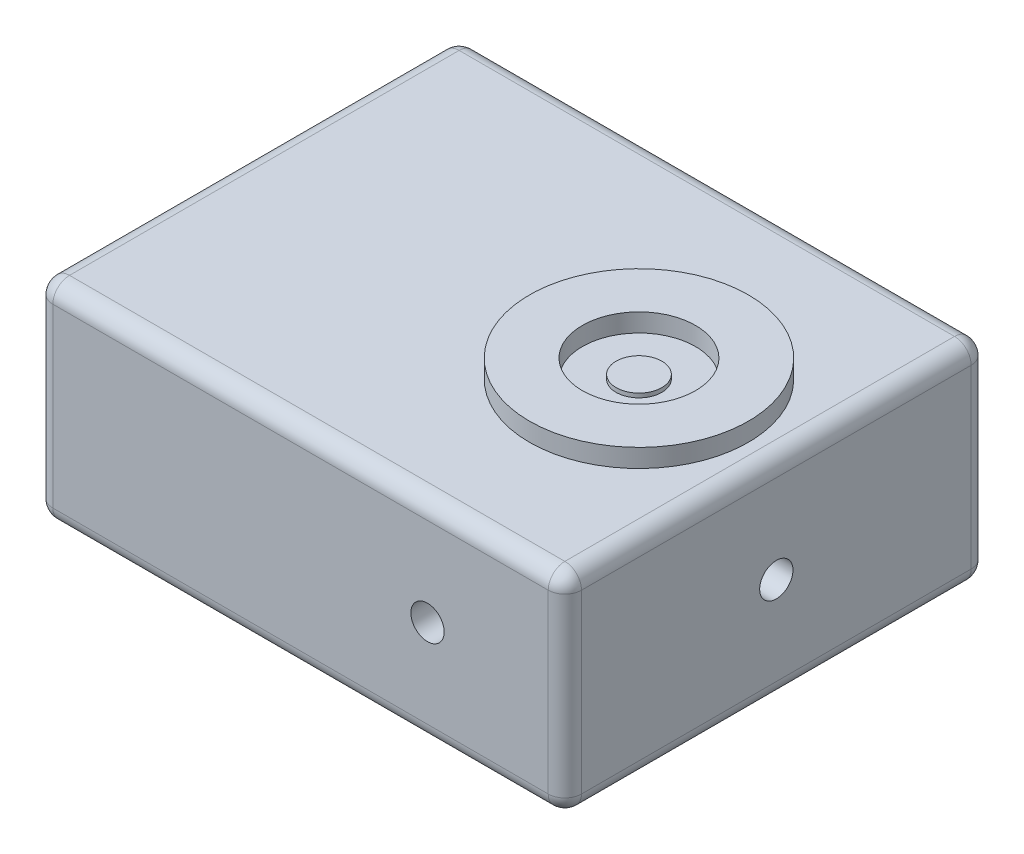
SolidWorks part; units mm, degrees
material "Stainless Steel (ferritic)"
ref_plane "Front Plane" through (0, 0, 0) normal (0, 0, 1) x (1, 0, 0)
ref_plane "Top Plane" through (0, 0, 0) normal (0, 1, 0) x (1, 0, 0)
ref_plane "Right Plane" through (0, 0, 0) normal (1, 0, 0) x (0, 0, -1)
sketch "Sketch1" plane through (0, 0, 0) normal (0, 1, 0) x (1, 0, 0)
  line L1 (-31.75, -25.4) -> (31.75, -25.4)
  line L2 (-31.75, -25.4) -> (-31.75, 25.4)
  line L3 (-31.75, 25.4) -> (31.75, 25.4)
  line L4 (31.75, -25.4) -> (31.75, 25.4)
  line L5 (-31.75, -25.4) -> (31.75, 25.4) construction
  line L6 (-31.75, 25.4) -> (31.75, -25.4) construction
  point P0 (0, 0)
  dimension "D1" = 63.5
  dimension "D2" = 50.8
extrude "Boss-Extrude1" add sketch "Sketch1" along normal blind 25.2
sketch "Sketch2" plane through (0, 25.2, 0) normal (0, 1, 0) x (1, 0, 0)
  line L0 (-31.75, -25.4) -> (31.75, -25.4) construction
  line L2 (31.75, -25.4) -> (31.75, 25.4) construction
  circle A0 centre (15.25, 0) radius 13.1445
  circle A1 centre (15.25, 0) radius 6.7945
  dimension "D1" = 26.289
  dimension "D2" = 13.589
  dimension "D3" = 25.4
  dimension "D4" = 16.5
extrude "Boss-Extrude2" add sketch "Sketch2" along normal blind 2.2
sketch "Sketch3" plane through (0, 0, 25.4) normal (0, 0, 1) x (1, 0, 0)
  line L0 (31.75, 25.2) -> (31.75, 0) construction
  circle A0 centre (15.25, 12.6) radius 2
  point P4 (31.75, 12.6)
  dimension "D1" = 4
  dimension "D2" = 16.5
extrude "Cut-Extrude1" cut sketch "Sketch3" against normal blind 5.5
sketch "Sketch4" plane through (31.75, 0, 0) normal (1, 0, 0) x (0, 0, -1)
  line L0 (-25.4, 25.2) -> (25.4, 25.2) construction
  line L1 (-25.4, 25.2) -> (-25.4, 0) construction
  circle A0 centre (0, 12.6) radius 2
  point P5 (0, 25.2)
  point P8 (-25.4, 12.6)
  dimension "D1" = 4
extrude "Cut-Extrude2" cut sketch "Sketch4" against normal blind 5.5
sketch "Sketch5" plane through (0, 0, -25.4) normal (0, 0, -1) x (-1, 0, 0)
  line L0 (-31.75, 25.2) -> (-31.75, 0) construction
  circle A0 centre (-15.25, 12.6) radius 2
  point P4 (-31.75, 12.6)
  dimension "D1" = 4
  dimension "D2" = 16.5
extrude "Cut-Extrude3" cut sketch "Sketch5" against normal blind 5.5
fillet "Fillet1" radius 2 12 edges at (31.75, 0, 0) (0, 0, -25.4) (-31.75, 0, 0) (0, 0, 25.4) (0, 25.2, -25.4) (-31.75, 25.2, 0) (0, 25.2, 25.4) (31.75, 12.6, 25.4) (-31.75, 12.6, 25.4) (-31.75, 12.6, -25.4) (31.75, 12.6, -25.4) (31.75, 25.2, 0)
sketch "Sketch6" plane through (0, 0, -25.4) normal (0, 0, -1) x (-1, 0, 0)
  line L0 (31.75, 23.2) -> (31.75, 2) construction
  line L1 (7.25, 2.5) -> (25.25, 2.5)
  line L2 (7.25, 2.5) -> (7.25, 14.5)
  line L3 (7.25, 14.5) -> (25.25, 14.5)
  line L4 (25.25, 2.5) -> (25.25, 14.5)
  line L5 (7.25, 2.5) -> (25.25, 14.5) construction
  line L6 (7.25, 14.5) -> (25.25, 2.5) construction
  line L7 (29.75, 0) -> (-29.75, 0) construction
  point P0 (16.25, 8.5)
  dimension "D1" = 18
  dimension "D2" = 12
  dimension "D3" = 6.5
  dimension "D4" = 2.5
extrude "Boss-Extrude3" add sketch "Sketch6" along normal blind 1
sketch "Sketch7" plane through (0, 25.2, 0) normal (0, 1, 0) x (1, 0, 0)
  circle A0 centre (15.25, 0) radius 2.75
  dimension "D1" = 5.5
extrude "Boss-Extrude4" add sketch "Sketch7" along normal blind 0.5
